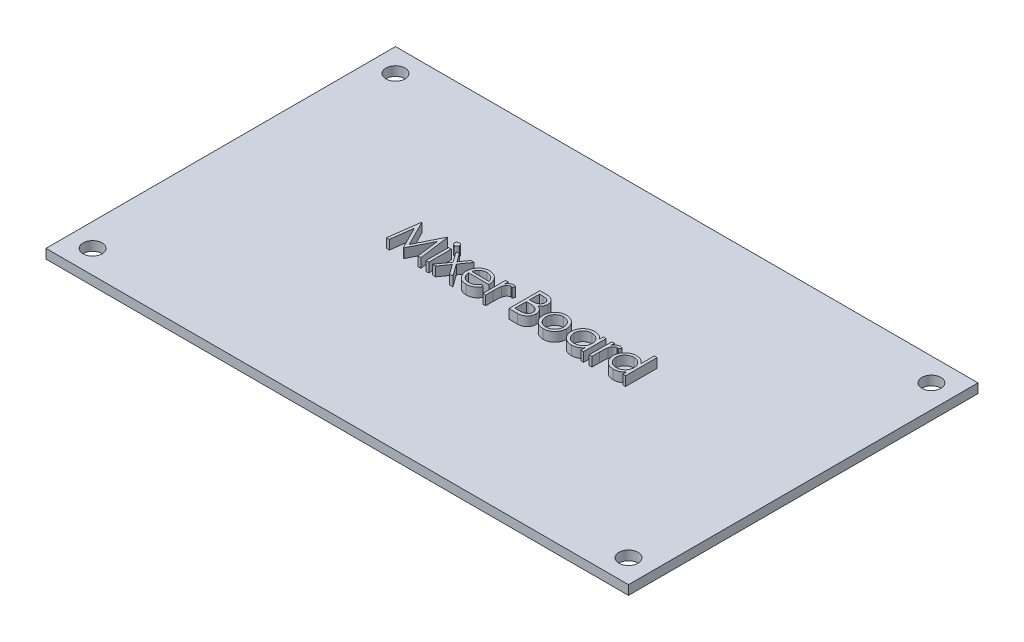
SolidWorks part; units mm, degrees
ref_plane "Front Plane" through (0, 0, 0) normal (0, 0, 1) x (1, 0, 0)
ref_plane "Top Plane" through (0, 0, 0) normal (0, 1, 0) x (1, 0, 0)
ref_plane "Right Plane" through (0, 0, 0) normal (1, 0, 0) x (0, 0, -1)
sketch "Sketch1" plane through (0, 0, 0) normal (0, 1, 0) x (1, 0, 0)
  line L1 (50, -30) -> (-50, -30)
  line L2 (50, -30) -> (50, 30)
  line L3 (50, 30) -> (-50, 30)
  line L4 (-50, -30) -> (-50, 30)
  line L5 (50, -30) -> (-50, 30) construction
  line L6 (50, 30) -> (-50, -30) construction
  point P0 (0, 0)
  dimension "D1" = 60
  dimension "D2" = 100
extrude "Boss-Extrude1" add sketch "Sketch1" along normal blind 1.6
hole_wizard "#4 Clearance Hole1" positions "Sketch3" profile "Sketch4" hole size "#4" standard "ANSI Inch" end condition through all
sketch "Sketch3" plane through (0, 1.6, 0) normal (0, 1, 0) x (1, 0, 0)
  line L0 (50, 30) -> (-50, 30) construction
  line L1 (-50, 30) -> (-50, -30) construction
  line L2 (50, -30) -> (50, 30) construction
  line L3 (-50, -30) -> (50, -30) construction
  point P0 (-46, 26)
  point P2 (46, 26)
  point P4 (46, -26)
  point P6 (-46, -26)
  point P15 (-45.1255, 26)
  point P16 (0, 0)
  point P27 (-44.9829, -26.147)
  dimension "D1" = 4
  dimension "D2" = 4
  dimension "D3" = 4
  dimension "D4" = 4
  dimension "D5" = 4
  dimension "D6" = 4
  dimension "D7" = 4
  dimension "D8" = 4
sketch "Sketch4" plane through (-46, 1.6, -26) normal (1, 0, 0) x (0, 0, 1)
  line L0 (0, 0) -> (0, 1.6)
  line L1 (0, 1.6) -> (1.6319, 1.6)
  line L2 (1.6319, 1.6) -> (1.6319, 0)
  line L5 (1.6319, 0) -> (0, 0)
  line L11 (0, -6.35) -> (0, 107.95) construction
  dimension "Thru Hole Dia." = 3.2639
  dimension "Thru Hole Depth" = 1.6
sketch "Sketch6" plane through (0, 1.6, 0) normal (0, 1, 0) x (1, 0, 0)
  text T0 "Mixer Board" font "Century Gothic" height in points 20
extrude "Boss-Extrude2" add sketch "Sketch6" along normal blind 1.6
